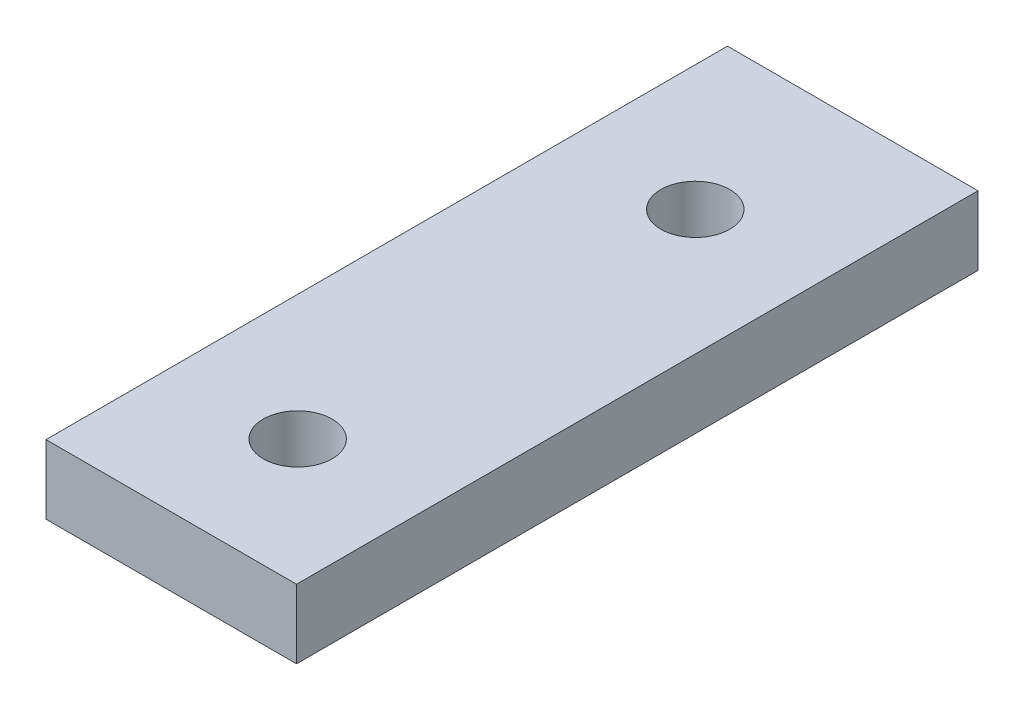
SolidWorks part; units mm, degrees
material "3mm Birch Ply Wood"
ref_plane "Front Plane" through (0, 0, 0) normal (0, 0, 1) x (1, 0, 0)
ref_plane "Top Plane" through (0, 0, 0) normal (0, 1, 0) x (1, 0, 0)
ref_plane "Right Plane" through (0, 0, 0) normal (1, 0, 0) x (0, 0, -1)
sketch "Sketch1" plane through (0, 0, 0) normal (0, 1, 0) x (1, 0, 0)
  line L0 (165.8891, 84.515) -> (165.8891, 54.865) construction
  line L3 (160.4391, 80.165) -> (160.4391, 57.865)
  line L6 (160.4391, 80.165) -> (160.4391, 84.515)
  line L8 (160.4391, 84.515) -> (171.3391, 84.515)
  line L10 (160.4391, 57.865) -> (160.4391, 54.865)
  line L12 (160.4391, 54.865) -> (171.3391, 54.865)
  line L14 (171.3391, 57.865) -> (171.3391, 54.865)
  line L15 (171.3391, 80.165) -> (171.3391, 84.515)
  line L16 (171.3391, 80.165) -> (171.3391, 57.865)
  circle A0 centre (165.8891, 77.665) radius 1.5
  circle A2 centre (165.8891, 60.365) radius 1.5
extrude "Boss-Extrude1" add sketch "Sketch1" along normal blind 3
